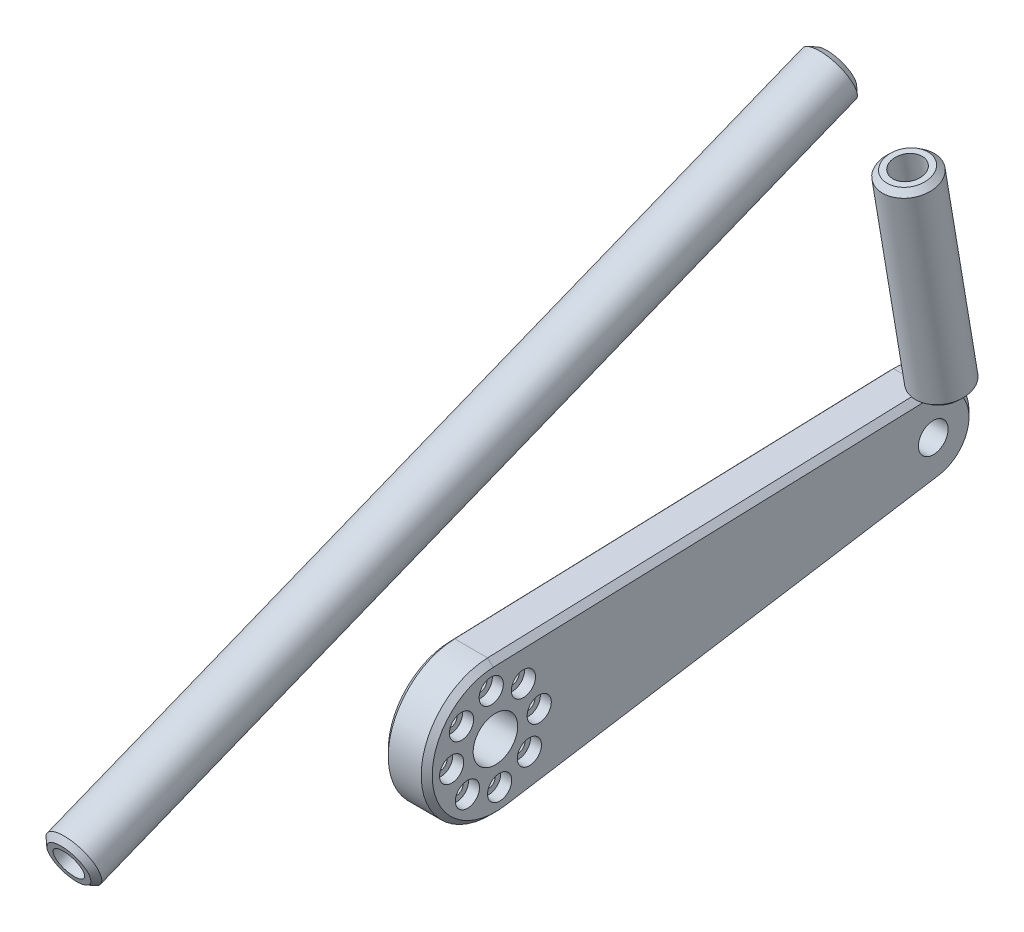
SolidWorks part; units mm, degrees
material "ABS PC"
ref_plane "Front" through (0, 0, 0) normal (0, 0, 1) x (1, 0, 0)
ref_plane "Top" through (0, 0, 0) normal (0, 1, 0) x (1, 0, 0)
ref_plane "Right" through (0, 0, 0) normal (1, 0, 0) x (0, 0, -1)
sketch "Sketch1" plane through (0, 0, 0) normal (1, 0, 0) x (0, 0, -1)
  line L0 (0, 0) -> (79.6326, 7.6586) construction
  line L1 (79.6326, 7.6586) -> (69.6846, 66.8282) construction
  line L2 (-97.45, 0) -> (69.6846, 66.8282) construction
  line L3 (69.6846, 66.8282) -> (134.6815, 92.817) construction
  line L4 (-35.25, 0) -> (-110.25, 0) construction
  line L5 (11.25, 0) -> (161.25, 0) construction
  line B0 (11.25, 0) -> (0, 0) construction
  line B1 (-35.25, 14.25) -> (11.25, 14.25) construction
  line B2 (-35.25, 14.25) -> (-35.25, -14.25) construction
  line B3 (-35.25, -14.25) -> (11.25, -14.25) construction
  line B4 (11.25, 14.25) -> (11.25, -14.25) construction
  dimension "100" = 80
  dimension "D2" = 97.45
  dimension "D3" = 180
  dimension "D4" = 60
  dimension "D5" = 250
  dimension "D6" = 75
  dimension "D7" = 150
sketch_block_instance "DYNAMIXEL 430 Front-1"
sketch_block "DYNAMIXEL 430 Front" parameters "D1"=46.5, "D2"=28.5, "D3"=11.25, "D4"=8, "D5"=8, "D6"=11, "D7"=11
sketch "Sketch2" plane through (0, 0, 0) normal (1, 0, 0) x (0, 0, -1)
  line L0 (-0.4167, 12.4931) -> (79.3826, 15.1545)
  line L1 (1.972, -12.3435) -> (80.8158, 0.2525)
  arc A0 (-0.4167, 12.4931) -> (1.972, -12.3435) centre (0, 0) ccw
  arc A1 (80.8158, 0.2525) -> (79.3826, 15.1545) centre (79.6326, 7.6586) ccw
  circle A2 centre (0, 0) radius 4.05
  circle A3 centre (79.6326, 7.6586) radius 2.7
  dimension "D1" = 25
  dimension "D2" = 15
  dimension "D3" = 8.1
  dimension "D4" = 5.4
extrude "Boss-Extrude1" add sketch "Sketch2" along normal blind 8
hole_wizard "CBORE for M2 SHCS1" positions "Sketch3" profile "Sketch4" counterbore size "M2" standard "ANSI Metric" end condition through all
sketch "Sketch3" plane through (8, 0, 0) normal (1, 0, 0) x (0, 0, -1)
  line L0 (0, 0) -> (7.9633, 0.7659) construction
  line L1 (0, 0) -> (79.6326, 7.6586) construction
  point P0 (7.9633, 0.7659)
  point P7 (6.1724, -5.0893)
  point P8 (0.7659, -7.9633)
  point P9 (-5.0893, -6.1724)
  point P10 (-7.9633, -0.7659)
  point P11 (-6.1724, 5.0893)
  point P12 (-0.7659, 7.9633)
  point P13 (5.0893, 6.1724)
  dimension "D2" = 8
  dimension "D1" = 8
sketch "Sketch4" plane through (8, 0.7659, -7.9633) normal (0, 1, 0) x (0, 0, -1)
  line L0 (0, 0) -> (0, 8)
  line L1 (0, 8) -> (1.2, 8)
  line L3 (1.2, 8) -> (1.2, 2)
  line L4 (1.2, 2) -> (2.2, 2)
  line L5 (2.2, 2) -> (2.2, 0)
  line L7 (2.2, 0) -> (0, 0)
  line L11 (0, -6.35) -> (0, 107.95) construction
  dimension "Thru Hole Dia." = 2.4
  dimension "Thru Hole Depth" = 8
  dimension "C'Bore Dia." = 4.4
  dimension "C'Bore Depth" = 2
ref_plane "Plane2" through (0, 13.2308, -78.6957) normal (0, -0.1658, 0.9862) x (1, 0, 0)
sketch "Sketch7" plane through (0, 13.2308, -78.6957) normal (0, -0.1658, 0.9862) x (1, 0, 0)
  line L0 (11.45, -5.6503) -> (11.45, 54.3497) construction
  line L1 (8, 1.7832) -> (8, 12.3892) construction
  line L2 (11.45, 20.3497) -> (13.45, 20.3497)
  line L3 (13.45, 20.3497) -> (13.45, 13.3497)
  line L4 (14.15, 5.3497) -> (16.2125, 5.3497)
  line L5 (16.2125, 5.3497) -> (16.2125, 43.3497)
  line L6 (16.2125, 43.3497) -> (14.15, 43.3497)
  line L7 (13.45, 35.3497) -> (13.45, 28.3497)
  line L8 (13.45, 28.3497) -> (11.45, 28.3497)
  line L9 (11.45, 20.3497) -> (11.45, 28.3497)
  line L10 (13.45, 35.3497) -> (14.15, 35.3497)
  line L11 (14.15, 35.3497) -> (14.15, 43.3497)
  line L12 (14.15, 5.3497) -> (14.15, 13.3497)
  line L13 (14.15, 13.3497) -> (13.45, 13.3497)
  dimension "D1" = 3.45
  dimension "D2" = 11
  dimension "D3" = 15
  dimension "D4" = 4
  dimension "D5" = 9.525
  dimension "D6" = 11
  dimension "D7" = 5.4
  dimension "D8" = 8
  dimension "D9" = 15
revolve "Revolve1" add sketch "Sketch7" angle 360 about L0
chamfer "Chamfer2" distance 1 angle 45 2 edges at (11.45, 19.296, -82.5054) (11.45, 56.7701, -76.205)
chamfer "Chamfer1" distance 1 angle 45 8 edges at (0, -6.0455, -41.3939) (0, 8.3766, -87.0981) (0, -1.1967, 12.4426) (0, 13.8238, -39.483) (8, -6.0455, -41.3939) (8, 8.3766, -87.0981) (8, -1.1967, 12.4426) (8, 13.8238, -39.483)
ref_plane "Plane3" through (0, 33.5941, 13.4325) normal (0, -0.9285, -0.3713) x (0, 0.3713, -0.9285)
sketch "Sketch8" plane through (0, 33.5941, 13.4325) normal (0, -0.9285, -0.3713) x (0, 0.3713, -0.9285)
  line L0 (-90.4848, 0) -> (89.5152, 0) construction
  line L1 (-45.4848, 0) -> (74.5152, 0)
  line L2 (74.5152, 0) -> (74.5152, 1.75)
  line L3 (74.5152, 1.75) -> (81.5152, 1.75)
  line L4 (89.5152, 2.7) -> (89.5152, 4.7625)
  line L5 (89.5152, 4.7625) -> (-60.4848, 4.7625)
  line L6 (-60.4848, 4.7625) -> (-60.4848, 2.7)
  line L7 (-52.4848, 1.75) -> (-45.4848, 1.75)
  line L8 (-45.4848, 1.75) -> (-45.4848, 0)
  line L9 (-52.4848, 1.75) -> (-52.4848, 2.7)
  line L10 (-52.4848, 2.7) -> (-60.4848, 2.7)
  line L11 (89.5152, 2.7) -> (81.5152, 2.7)
  line L12 (81.5152, 2.7) -> (81.5152, 1.75)
  line L13 (-90.4848, 0) -> (89.5152, 0) construction
  dimension "D1" = 120
  dimension "D2" = 3.5
  dimension "D3" = 15
  dimension "D4" = 9.525
  dimension "D5" = 15
  dimension "D6" = 5.4
  dimension "D7" = 8
revolve "Revolve2" add sketch "Sketch8" angle 360 about L0
chamfer "Chamfer3" distance 1 angle 45 2 edges at (0, 62.4061, -71.4528) (0, 6.7159, 67.8261)
